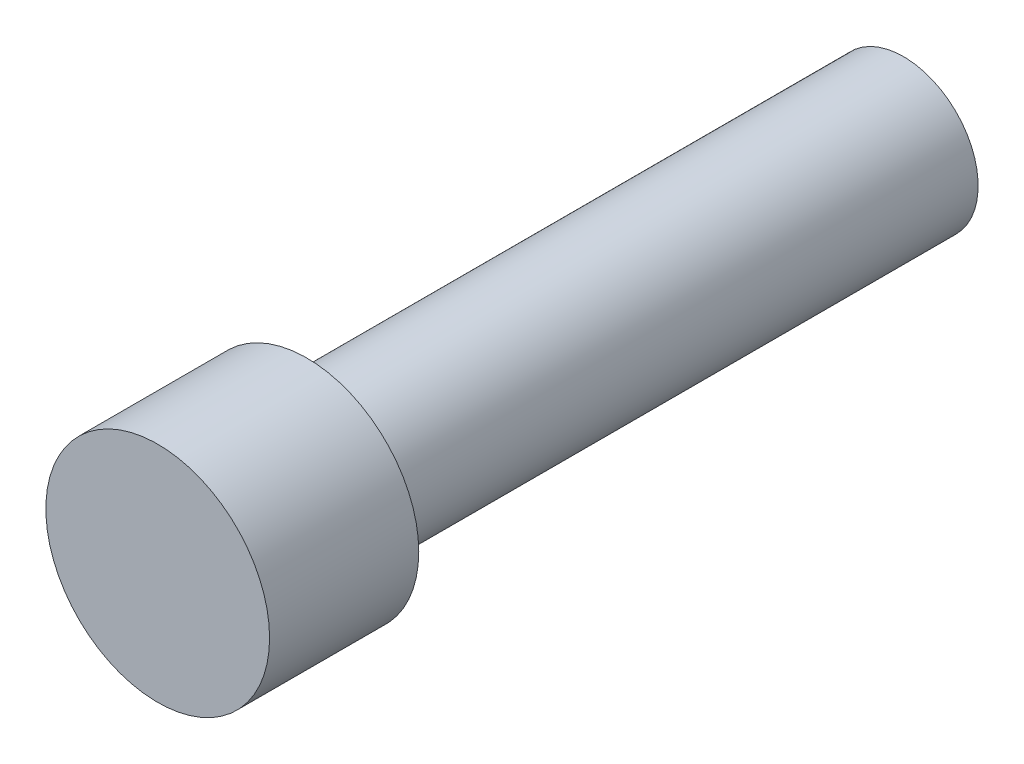
SolidWorks part; units mm, degrees
ref_plane "前视基准面" through (0, 0, 0) normal (0, 0, 1) x (1, 0, 0)
ref_plane "上视基准面" through (0, 0, 0) normal (0, 1, 0) x (1, 0, 0)
ref_plane "右视基准面" through (0, 0, 0) normal (1, 0, 0) x (0, 0, -1)
sketch "草图1" plane through (0, 0, 0) normal (0, 0, 1) x (1, 0, 0)
  circle A0 centre (0, 0) radius 1.5
  dimension "D1" = 3
extrude "凸台-拉伸1" add sketch "草图1" along normal blind 2
sketch "草图2" plane through (0, 0, 0) normal (0, 0, -1) x (-1, 0, 0)
  circle A0 centre (0, 0) radius 1
  dimension "D1" = 2
extrude "凸台-拉伸3" add sketch "草图2" along normal blind 8
